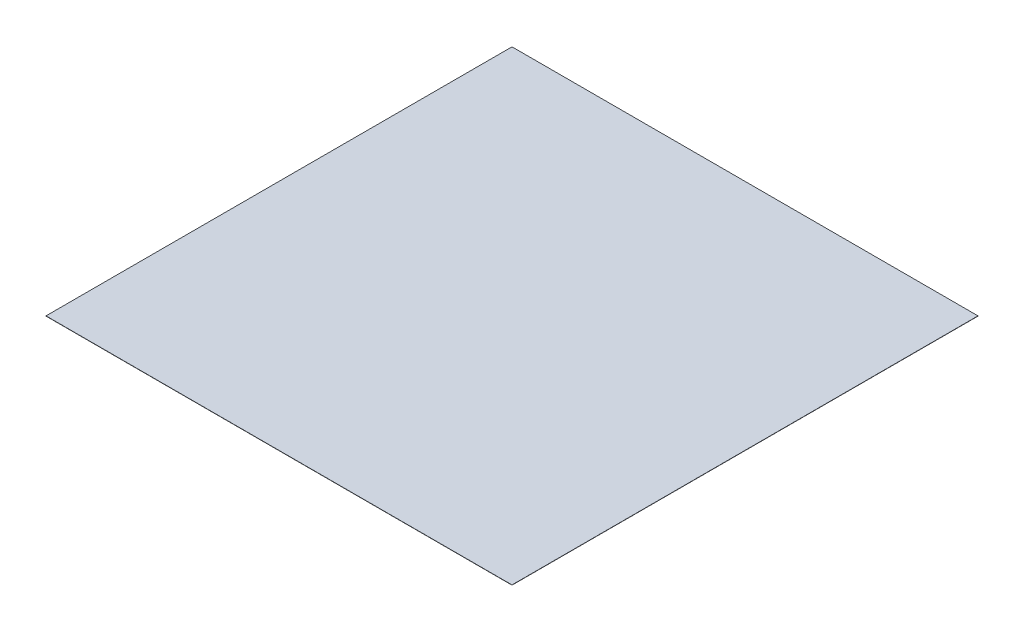
SolidWorks part; units mm, degrees
ref_plane "Front Plane" through (0, 0, 0) normal (0, 0, 1) x (1, 0, 0)
ref_plane "Top Plane" through (0, 0, 0) normal (0, 1, 0) x (1, 0, 0)
ref_plane "Right Plane" through (0, 0, 0) normal (1, 0, 0) x (0, 0, -1)
sketch "Sketch1" plane through (0, 0, 0) normal (0, 1, 0) x (1, 0, 0)
  line L1 (-1000, 1000) -> (1000, 1000)
  line L2 (-1000, 1000) -> (-1000, -1000)
  line L3 (-1000, -1000) -> (1000, -1000)
  line L4 (1000, 1000) -> (1000, -1000)
  line L5 (-1000, 1000) -> (1000, -1000) construction
  line L6 (-1000, -1000) -> (1000, 1000) construction
  point P0 (0, 0)
  dimension "D1" = 2000
  dimension "D2" = 2000
extrude "Boss-Extrude1" add sketch "Sketch1" along normal blind 1
